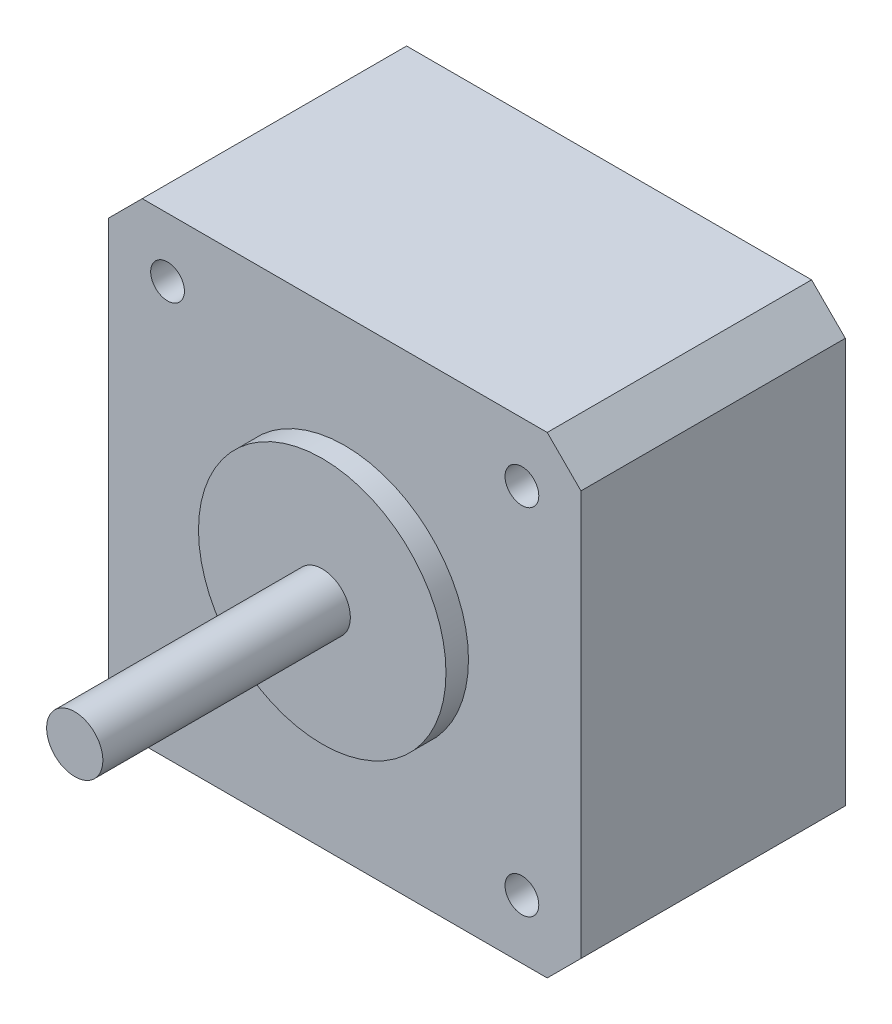
SolidWorks part; units mm, degrees
ref_plane "Front Plane" through (0, 0, 0) normal (0, 0, 1) x (1, 0, 0)
ref_plane "Top Plane" through (0, 0, 0) normal (0, 1, 0) x (1, 0, 0)
ref_plane "Right Plane" through (0, 0, 0) normal (1, 0, 0) x (0, 0, -1)
sketch "Sketch1" plane through (0, 0, 0) normal (0, 0, 1) x (1, 0, 0)
  line L1 (-21, 21) -> (21, 21)
  line L2 (-21, 21) -> (-21, -21)
  line L3 (-21, -21) -> (21, -21)
  line L4 (21, 21) -> (21, -21)
  line L5 (-21, 21) -> (21, -21) construction
  line L6 (-21, -21) -> (21, 21) construction
  point P0 (0, 0)
  dimension "D1" = 42
  dimension "D2" = 42
extrude "Boss-Extrude1" add sketch "Sketch1" along normal blind 23.5
sketch "Sketch2" plane through (0, 0, 23.5) normal (0, 0, 1) x (1, 0, 0)
  circle A0 centre (0, 0) radius 11
extrude "Boss-Extrude2" add sketch "Sketch2" along normal blind 2
sketch "Sketch3" plane through (0, 0, 25.5) normal (0, 0, 1) x (1, 0, 0)
  circle A0 centre (0, 0) radius 2.5
extrude "Boss-Extrude3" add sketch "Sketch3" along normal blind 22
chamfer "Chamfer1" distance 3 angle 45 4 edges at (-21, -21, 11.75) (21, -21, 11.75) (21, 21, 11.75) (-21, 21, 11.75)
sketch "Sketch4" plane through (0, 0, 23.5) normal (0, 0, 1) x (1, 0, 0)
  line L1 (-15.75, -15.75) -> (15.75, -15.75) construction
  line L2 (-15.75, -15.75) -> (-15.75, 15.75) construction
  line L3 (-15.75, 15.75) -> (15.75, 15.75) construction
  line L4 (15.75, -15.75) -> (15.75, 15.75) construction
  line L5 (-15.75, -15.75) -> (15.75, 15.75) construction
  line L6 (-15.75, 15.75) -> (15.75, -15.75) construction
  circle A0 centre (-15.75, 15.75) radius 1.5
  circle A1 centre (15.75, 15.75) radius 1.5
  circle A2 centre (-15.75, -15.75) radius 1.5
  circle A3 centre (15.75, -15.75) radius 1.5
  point P0 (0, 0)
  dimension "D1" = 31.5
  dimension "D2" = 31.5
extrude "Cut-Extrude1" cut sketch "Sketch4" against normal blind 10
